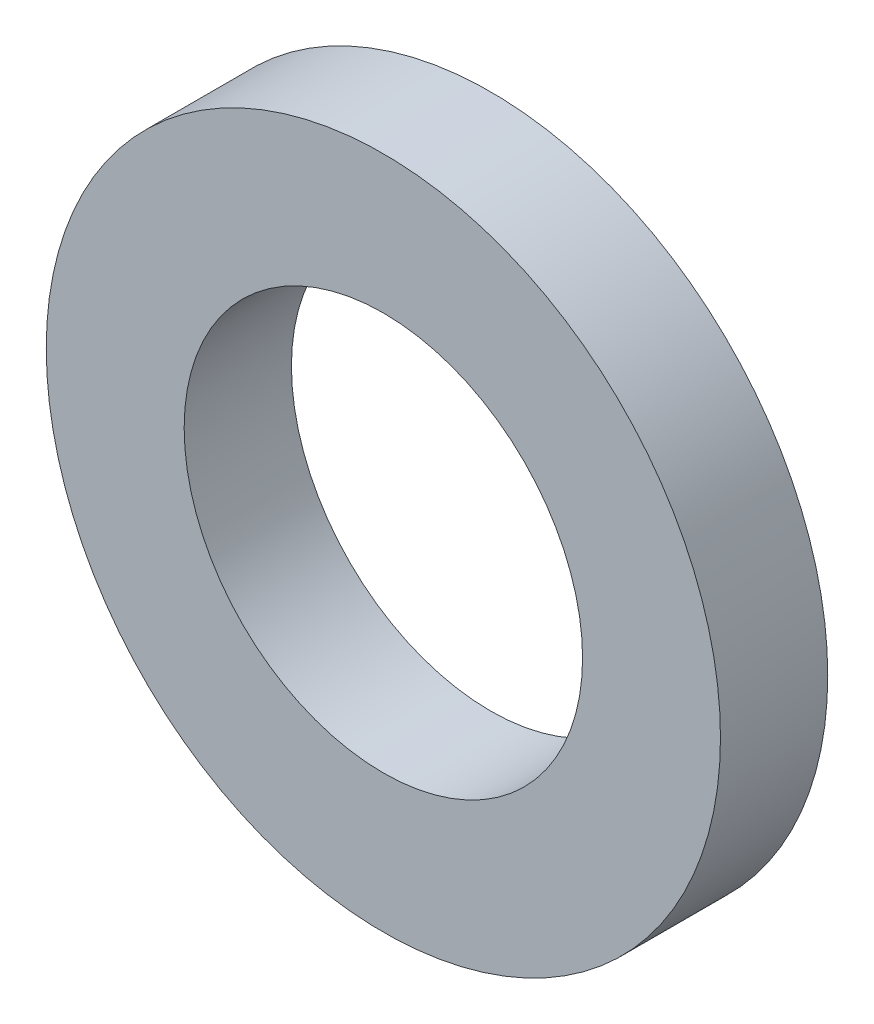
SolidWorks part; units mm, degrees
ref_plane "Front Plane" through (0, 0, 0) normal (0, 0, 1) x (1, 0, 0)
ref_plane "Top Plane" through (0, 0, 0) normal (0, 1, 0) x (1, 0, 0)
ref_plane "Right Plane" through (0, 0, 0) normal (1, 0, 0) x (0, 0, -1)
sketch "Sketch1" plane through (0, 0, 0) normal (0, 0, 1) x (1, 0, 0)
  circle A0 centre (0, 0) radius 11
  dimension "D1" = 22
extrude "Boss-Extrude1" add sketch "Sketch1" along normal blind 3.5
sketch "Sketch4" plane through (0, 0, 0) normal (0, 0, -1) x (-1, 0, 0)
  circle A0 centre (0, 0) radius 6.5
  dimension "D1" = 13
extrude "Cut-Extrude2" cut sketch "Sketch4" against normal blind 3.5
